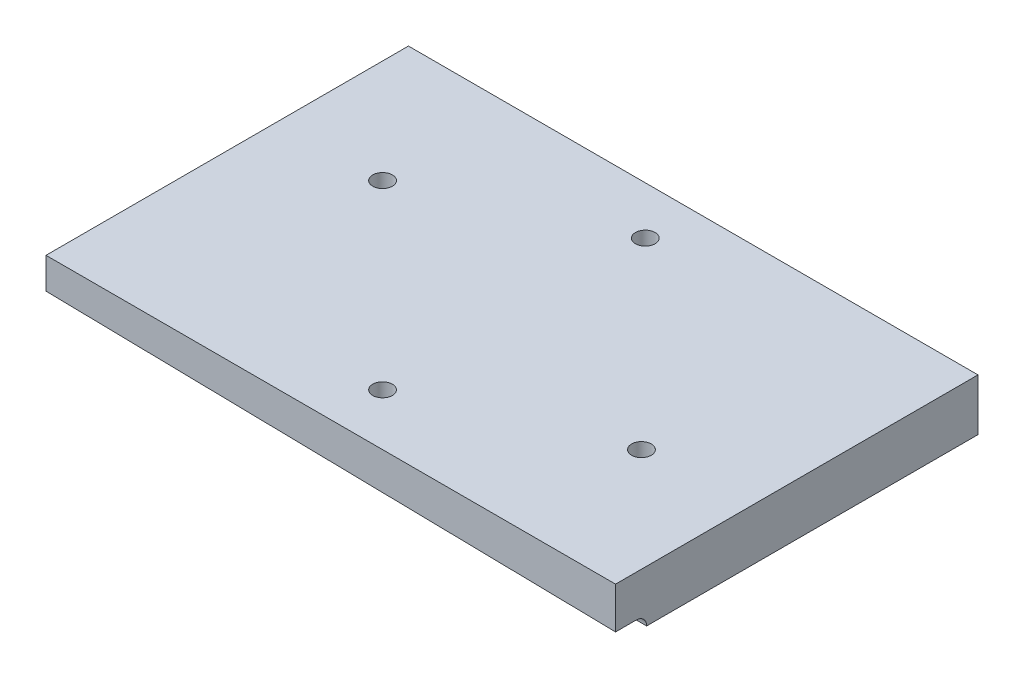
SolidWorks part; units mm, degrees
ref_plane "Front Plane" through (0, 0, 0) normal (0, 0, 1) x (1, 0, 0)
ref_plane "Top Plane" through (0, 0, 0) normal (0, 1, 0) x (1, 0, 0)
ref_plane "Right Plane" through (0, 0, 0) normal (1, 0, 0) x (0, 0, -1)
sketch "Sketch1" plane through (0, 0, 0) normal (0, 1, 0) x (1, 0, 0)
  line L1 (-45.1306, -30.6096) -> (64.8694, -30.6096)
  line L2 (-45.1306, -30.6096) -> (-45.1306, 39.3904)
  line L3 (-45.1306, 39.3904) -> (64.8694, 39.3904)
  line L4 (64.8694, -30.6096) -> (64.8694, 39.3904)
  dimension "D1" = 70
  dimension "D2" = 110
extrude "Boss-Extrude1" add sketch "Sketch1" along normal blind 10 contours L2 L1 L4 L3
sketch "Sketch6" plane through (0, 0, 0) normal (0, -1, 0) x (1, 0, 0)
  line L0 (64.8694, -4.3904) -> (9.8694, -4.3904)
  line L1 (64.8694, 30.6096) -> (64.8694, -39.3904) construction
  line L2 (9.8694, -4.3904) -> (9.8694, 20.6096)
  line L5 (9.8694, -4.3904) -> (9.8694, -30.1287)
  dimension "D1" = 55
  dimension "D2" = 25
sketch "Sketch15" plane through (0, 0, 0) normal (0, -1, 0) x (1, 0, 0)
  line L0 (9.8694, -4.3904) -> (-25.1306, -4.3904)
  line L1 (-25.1306, -4.3904) -> (44.8694, -4.3904)
  point P4 (0, 0)
  point P5 (0, 0)
  point P6 (0, 0)
sketch "Sketch5" plane through (0, 10, 0) normal (0, 1, 0) x (1, 0, 0)
  circle A0 centre (9.8694, -20.6096) radius 1.9
  point P2 (9.8694, -20.6096)
  dimension "D1" = 3.8
extrude "Cut-Extrude4" cut sketch "Sketch5" against normal through all
sketch "Sketch10" plane through (-45.1306, 0, 0) normal (-1, 0, 0) x (0, 0, 1)
  line L0 (30.6096, 0) -> (30.6096, 4)
  line L1 (30.6096, 10) -> (30.6096, 0) construction
  line L2 (30.6096, 4) -> (30.4899, 3.8725)
  line L3 (30.6096, 0) -> (24.6096, 0)
  line L4 (30.6096, 0) -> (-39.3904, 0) construction
  line L5 (24.6096, 0) -> (24.6096, 4)
  line L6 (24.6096, 4) -> (30.6096, 4)
sketch "Sketch12" plane through (64.8694, 0, 0) normal (1, 0, 0) x (0, 0, -1)
  line L0 (-30.6096, 0) -> (-30.6096, 2)
  line L1 (-30.6096, 10) -> (-30.6096, 0) construction
  line L2 (-30.6096, 2) -> (-24.6096, 2)
  line L3 (-24.6096, 2) -> (-24.6096, 0)
  line L4 (-30.6096, 0) -> (39.3904, 0) construction
  line L5 (-24.6096, 0) -> (-30.6096, 0)
sketch "Sketch14" plane through (0, 0, 30.6096) normal (0, 0, 1) x (1, 0, 0)
  line L0 (-45.1306, 0) -> (-45.1306, 4)
  line L1 (-45.1306, 4) -> (64.8694, 2)
  line L2 (64.8694, 2) -> (64.8694, 0)
  line L3 (64.8694, 0) -> (-45.1306, 0)
extrude "Cut-Extrude6" cut sketch "Sketch14" against normal blind 6
sketch "Sketch17" plane through (0, 0, 0) normal (0, -1, 0) x (-1, 0, 0)
  circle A0 centre (-9.8694, 30.1287) radius 1.9
  point P2 (-1.2722, -16.961)
  point P4 (-9.8694, 30.1287)
  dimension "D1" = 3.8
extrude "Cut-Extrude8" cut sketch "Sketch17" against normal through all
sketch "Sketch22" plane through (0, 0, 0) normal (0, -1, 0) x (-1, 0, 0)
  line L0 (-44.8694, 4.3904) -> (-44.8694, -5.6096)
  dimension "D1" = 10
sketch "Sketch23" plane through (0, 0, 0) normal (0, -1, 0) x (-1, 0, 0)
  line L0 (25.1306, 4.3904) -> (25.1306, 14.3904)
  dimension "D1" = 10
fillet "Fillet1" radius 2 1 edges at (9.8694, 3, 24.6096)
sketch "Sketch24" plane through (0, 0, 0) normal (0, -1, 0) x (1, 0, 0)
  circle A0 centre (44.8694, 5.6096) radius 1.9
  point P3 (43.191, 6.4966)
  dimension "D1" = 3.8
extrude "Cut-Extrude12" cut sketch "Sketch24" against normal through all
sketch "Sketch25" plane through (0, 0, 0) normal (0, -1, 0) x (1, 0, 0)
  circle A0 centre (-25.1306, -14.3904) radius 1.9
  dimension "D1" = 3.8
extrude "Cut-Extrude13" cut sketch "Sketch25" against normal through all
ref_plane "Plane1" through (0, -5, 0) normal (0, 1, 0) x (1, 0, 0)
